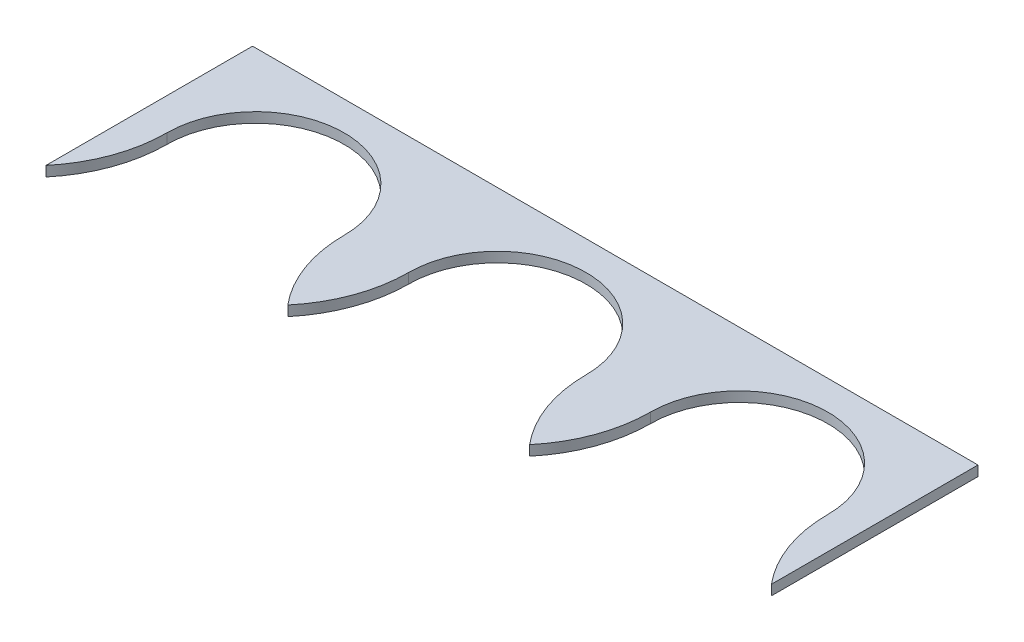
SolidWorks part; units mm, degrees
ref_plane "Front Plane" through (0, 0, 0) normal (0, 0, 1) x (1, 0, 0)
ref_plane "Top Plane" through (0, 0, 0) normal (0, 1, 0) x (1, 0, 0)
ref_plane "Right Plane" through (0, 0, 0) normal (1, 0, 0) x (0, 0, -1)
sketch "Sketch1" plane through (0, 0, 0) normal (0, 1, 0) x (1, 0, 0)
  line L0 (152.4, -130.175) -> (152.4, 0)
  line L1 (0, 0) -> (457.2, 0)
  line L2 (0, 0) -> (0, -130.175)
  line L3 (0, -130.175) -> (457.2, -130.175)
  line L4 (457.2, 0) -> (457.2, -130.175)
  line L5 (304.8, -130.175) -> (304.8, 0)
  circle A0 centre (76.2, -74.295) radius 55.88
  circle A1 centre (228.6, -74.295) radius 55.88
  circle A2 centre (381, -74.295) radius 55.88
  arc A3 (0, -130.175) -> (20.32, -74.295) centre (-66.675, -74.295) ccw
  arc A4 (132.08, -74.295) -> (152.4, -130.175) centre (219.075, -74.295) ccw
  arc A5 (152.4, -130.175) -> (172.72, -74.295) centre (85.725, -74.295) ccw
  arc A6 (284.48, -74.295) -> (304.8, -130.175) centre (371.475, -74.295) ccw
  arc A7 (325.12, -74.295) -> (304.8, -130.175) centre (238.125, -74.295) cw
  arc A8 (436.88, -74.295) -> (457.2, -130.175) centre (523.875, -74.295) ccw
  dimension "D3" = 111.76
  dimension "D4" = 111.76
  dimension "D5" = 111.76
  dimension "D1" = 457.2
  dimension "D2" = 130.175
  dimension "D6" = 152.4
  dimension "D7" = 152.4
  dimension "D8" = 76.2
  dimension "D9" = 76.2
  dimension "D10" = 76.2
  dimension "D29" = 0
  dimension "D30" = 0
extrude "Boss-Extrude1" add sketch "Sketch1" against normal blind 6.35
